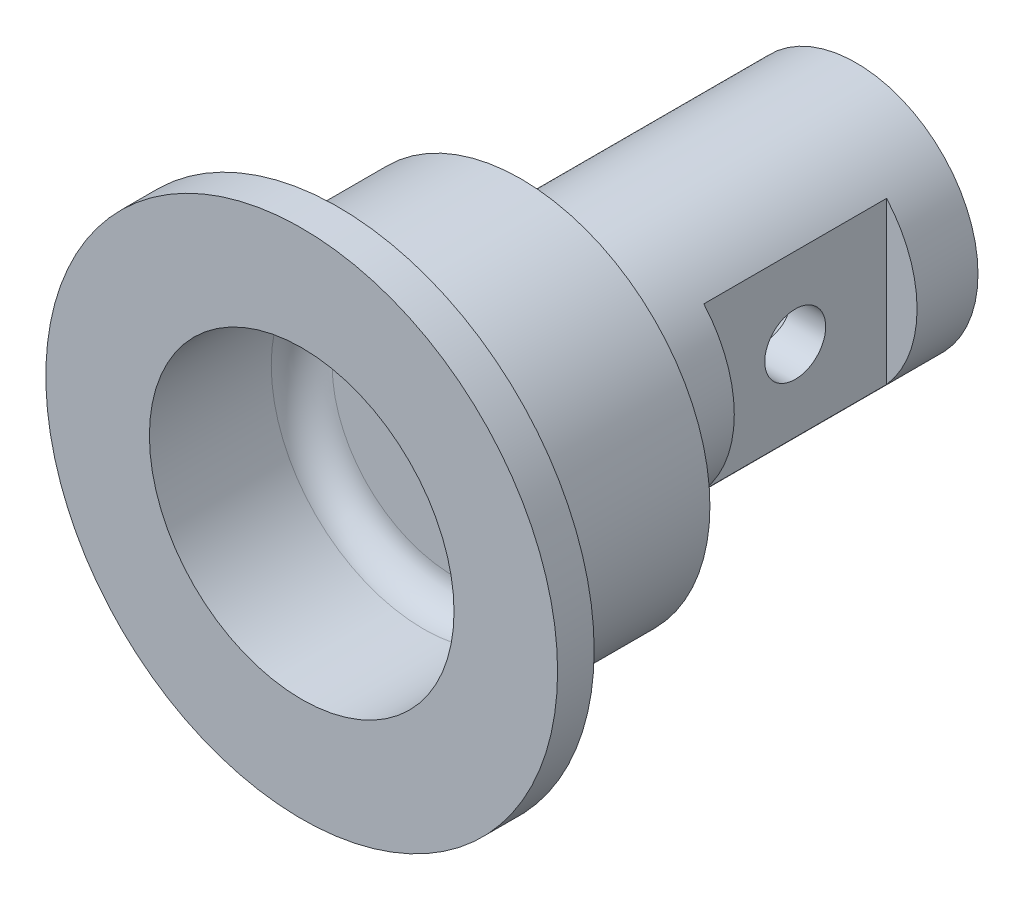
SolidWorks part; units mm, degrees
ref_plane "Alzado" through (0, 0, 0) normal (0, 0, 1) x (1, 0, 0)
ref_plane "Planta" through (0, 0, 0) normal (0, 1, 0) x (1, 0, 0)
ref_plane "Vista lateral" through (0, 0, 0) normal (1, 0, 0) x (0, 0, -1)
sketch "Croquis1" plane through (0, 0, 0) normal (0, 1, 0) x (1, 0, 0)
  line L0 (25, 0) -> (42, 0)
  line L1 (42, 0) -> (42, 6)
  line L2 (42, 6) -> (31, 6)
  line L3 (31, 6) -> (31, 36)
  line L4 (31, 36) -> (20, 36)
  line L5 (20, 36) -> (20, 91)
  line L6 (20, 91) -> (9, 91)
  line L7 (9, 91) -> (9, 25)
  line L8 (9, 25) -> (25, 25)
  line L9 (25, 25) -> (25, 0)
  line L10 (0, -3.6776) -> (0, 142.2666) construction
  dimension "D1" = 42
  dimension "D2" = 25
  dimension "D3" = 9
  dimension "D4" = 20
  dimension "D5" = 31
  dimension "D6" = 6
  dimension "D7" = 25
  dimension "D8" = 30
  dimension "D9" = 55
revolve "Revolución1" add sketch "Croquis1" angle 360 about L10
fillet "Redondeo1" radius 5 3 edges at (25, 0, -25) (20, 0, -36) (31, 0, -6)
sketch "Croquis2" plane through (0, 0, 0) normal (0, 1, 0) x (1, 0, 0)
  line L0 (20, 81) -> (15, 81)
  line L1 (20, 41) -> (20, 91) construction
  line L2 (15, 81) -> (15, 51)
  line L3 (15, 51) -> (20, 51)
  line L4 (20, 51) -> (20, 81)
  line L5 (20, 91) -> (-20, 91) construction
  dimension "D1" = 10
  dimension "D2" = 30
  dimension "D3" = 5
extrude "Cortar-Extruir1" cut sketch "Croquis2" against normal up to next and the other way up to next
sketch "Croquis3" plane through (15, 0, 0) normal (1, 0, 0) x (0, 0, -1)
  line L1 (25, 9) -> (25, -9) construction
  circle A0 centre (66, 0) radius 5
  dimension "D1" = 10
  dimension "D2" = 41
extrude "Cortar-Extruir3" cut sketch "Croquis3" against normal up to next
mirror "Simetría2" about plane through (0, 0, 0) normal (1, 0, 0) of "Cortar-Extruir3", "Cortar-Extruir1"
